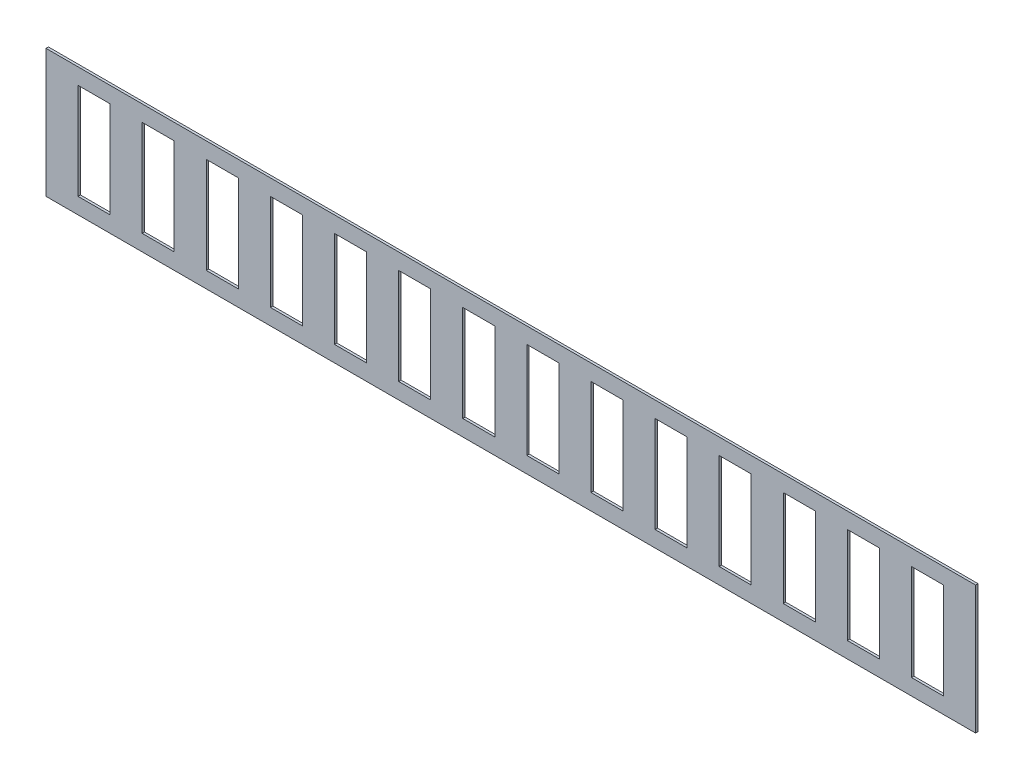
SolidWorks part; units mm, degrees
ref_plane "Front Plane" through (0, 0, 0) normal (0, 0, 1) x (1, 0, 0)
ref_plane "Top Plane" through (0, 0, 0) normal (0, 1, 0) x (1, 0, 0)
ref_plane "Right Plane" through (0, 0, 0) normal (1, 0, 0) x (0, 0, -1)
other "Configuration Table"
sketch "Sketch1" plane through (0, 0, 0) normal (0, 0, 1) x (1, 0, 0)
  line L1 (60, 30) -> (640, 30)
  line L2 (60, 30) -> (60, 110)
  line L3 (60, 110) -> (640, 110)
  line L4 (640, 30) -> (640, 110)
extrude "OVEN_plint_izgara_paneli_1" add sketch "Sketch1" along normal blind 1.5 from offset 18.5 separate body
sketch "Sketch2" plane through (0, 0, 0) normal (0, 0, 1) x (1, 0, 0)
  line L1 (80, 40) -> (100, 40)
  line L2 (80, 40) -> (80, 100)
  line L3 (80, 100) -> (100, 100)
  line L4 (100, 40) -> (100, 100)
extrude "OVEN_plint_izgara_paneli_2" cut sketch "Sketch2" along normal blind 4 from offset 17
sketch "Sketch3" plane through (0, 0, 0) normal (0, 0, 1) x (1, 0, 0)
  line L1 (120, 40) -> (140, 40)
  line L2 (120, 40) -> (120, 100)
  line L3 (120, 100) -> (140, 100)
  line L4 (140, 40) -> (140, 100)
extrude "OVEN_plint_izgara_paneli_3" cut sketch "Sketch3" along normal blind 4 from offset 17
sketch "Sketch4" plane through (0, 0, 0) normal (0, 0, 1) x (1, 0, 0)
  line L1 (160, 40) -> (180, 40)
  line L2 (160, 40) -> (160, 100)
  line L3 (160, 100) -> (180, 100)
  line L4 (180, 40) -> (180, 100)
extrude "OVEN_plint_izgara_paneli_4" cut sketch "Sketch4" along normal blind 4 from offset 17
sketch "Sketch5" plane through (0, 0, 0) normal (0, 0, 1) x (1, 0, 0)
  line L1 (200, 40) -> (220, 40)
  line L2 (200, 40) -> (200, 100)
  line L3 (200, 100) -> (220, 100)
  line L4 (220, 40) -> (220, 100)
extrude "OVEN_plint_izgara_paneli_5" cut sketch "Sketch5" along normal blind 4 from offset 17
sketch "Sketch6" plane through (0, 0, 0) normal (0, 0, 1) x (1, 0, 0)
  line L1 (240, 40) -> (260, 40)
  line L2 (240, 40) -> (240, 100)
  line L3 (240, 100) -> (260, 100)
  line L4 (260, 40) -> (260, 100)
extrude "OVEN_plint_izgara_paneli_6" cut sketch "Sketch6" along normal blind 4 from offset 17
sketch "Sketch7" plane through (0, 0, 0) normal (0, 0, 1) x (1, 0, 0)
  line L1 (280, 40) -> (300, 40)
  line L2 (280, 40) -> (280, 100)
  line L3 (280, 100) -> (300, 100)
  line L4 (300, 40) -> (300, 100)
extrude "OVEN_plint_izgara_paneli_7" cut sketch "Sketch7" along normal blind 4 from offset 17
sketch "Sketch8" plane through (0, 0, 0) normal (0, 0, 1) x (1, 0, 0)
  line L1 (320, 40) -> (340, 40)
  line L2 (320, 40) -> (320, 100)
  line L3 (320, 100) -> (340, 100)
  line L4 (340, 40) -> (340, 100)
extrude "OVEN_plint_izgara_paneli_8" cut sketch "Sketch8" along normal blind 4 from offset 17
sketch "Sketch9" plane through (0, 0, 0) normal (0, 0, 1) x (1, 0, 0)
  line L1 (360, 40) -> (380, 40)
  line L2 (360, 40) -> (360, 100)
  line L3 (360, 100) -> (380, 100)
  line L4 (380, 40) -> (380, 100)
extrude "OVEN_plint_izgara_paneli_9" cut sketch "Sketch9" along normal blind 4 from offset 17
sketch "Sketch10" plane through (0, 0, 0) normal (0, 0, 1) x (1, 0, 0)
  line L1 (400, 40) -> (420, 40)
  line L2 (400, 40) -> (400, 100)
  line L3 (400, 100) -> (420, 100)
  line L4 (420, 40) -> (420, 100)
extrude "OVEN_plint_izgara_paneli_10" cut sketch "Sketch10" along normal blind 4 from offset 17
sketch "Sketch11" plane through (0, 0, 0) normal (0, 0, 1) x (1, 0, 0)
  line L1 (440, 40) -> (460, 40)
  line L2 (440, 40) -> (440, 100)
  line L3 (440, 100) -> (460, 100)
  line L4 (460, 40) -> (460, 100)
extrude "OVEN_plint_izgara_paneli_11" cut sketch "Sketch11" along normal blind 4 from offset 17
sketch "Sketch12" plane through (0, 0, 0) normal (0, 0, 1) x (1, 0, 0)
  line L1 (480, 40) -> (500, 40)
  line L2 (480, 40) -> (480, 100)
  line L3 (480, 100) -> (500, 100)
  line L4 (500, 40) -> (500, 100)
extrude "OVEN_plint_izgara_paneli_12" cut sketch "Sketch12" along normal blind 4 from offset 17
sketch "Sketch13" plane through (0, 0, 0) normal (0, 0, 1) x (1, 0, 0)
  line L1 (520, 40) -> (540, 40)
  line L2 (520, 40) -> (520, 100)
  line L3 (520, 100) -> (540, 100)
  line L4 (540, 40) -> (540, 100)
extrude "OVEN_plint_izgara_paneli_13" cut sketch "Sketch13" along normal blind 4 from offset 17
sketch "Sketch14" plane through (0, 0, 0) normal (0, 0, 1) x (1, 0, 0)
  line L1 (560, 40) -> (580, 40)
  line L2 (560, 40) -> (560, 100)
  line L3 (560, 100) -> (580, 100)
  line L4 (580, 40) -> (580, 100)
extrude "OVEN_plint_izgara_paneli_14" cut sketch "Sketch14" along normal blind 4 from offset 17
sketch "Sketch15" plane through (0, 0, 0) normal (0, 0, 1) x (1, 0, 0)
  line L1 (600, 40) -> (620, 40)
  line L2 (600, 40) -> (600, 100)
  line L3 (600, 100) -> (620, 100)
  line L4 (620, 40) -> (620, 100)
extrude "OVEN_plint_izgara_paneli_15" cut sketch "Sketch15" along normal blind 4 from offset 17
